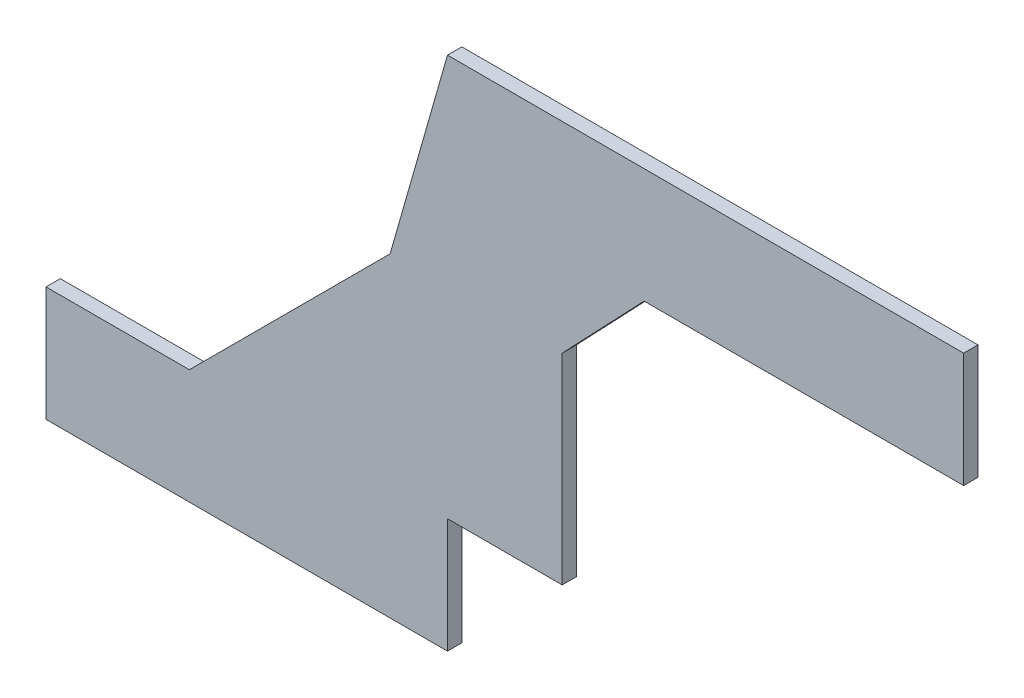
SolidWorks part; units mm, degrees
ref_plane "Front Plane" through (0, 0, 0) normal (0, 0, 1) x (1, 0, 0)
ref_plane "Top Plane" through (0, 0, 0) normal (0, 1, 0) x (1, 0, 0)
ref_plane "Right Plane" through (0, 0, 0) normal (1, 0, 0) x (0, 0, -1)
sketch "Sketch1" plane through (0, 0, 0) normal (0, 0, 1) x (1, 0, 0)
  line L0 (0, 0) -> (76.2, 0) construction
  line L1 (76.2, 0) -> (76.2, 88.9) construction
  line L2 (76.2, 88.9) -> (203.2, 88.9) construction
  line L3 (0, -12.7) -> (88.9, -12.7)
  line L4 (88.9, -12.7) -> (88.9, 12.7)
  line L5 (132.4429, 76.2) -> (203.2, 76.2)
  line L6 (0, 12.7) -> (31.75, 12.7)
  line L7 (114.3, 12.7) -> (114.3, 57.15)
  line L8 (88.9, 101.6) -> (203.2, 101.6)
  line L9 (0, -12.7) -> (0, 12.7)
  line L10 (203.2, 76.2) -> (203.2, 101.6)
  line L11 (76.2, 57.15) -> (88.9, 101.6)
  line L12 (88.9, 12.7) -> (114.3, 12.7)
  line L13 (114.3, 57.15) -> (132.4429, 76.2)
  line L14 (76.2, 57.15) -> (31.75, 12.7)
  line L16 (0, 12.7) -> (63.5, 12.7) construction
  line L17 (63.5, 101.6) -> (203.2, 101.6) construction
  line L18 (63.5, 12.7) -> (63.5, 101.6) construction
  line L19 (88.9, 76.2) -> (203.2, 76.2) construction
  line L20 (88.9, -12.7) -> (88.9, 76.2) construction
  dimension "D1" = 76.2
  dimension "D2" = 88.9
  dimension "D3" = 127
  dimension "D6" = 44.45
  dimension "D4" = 12.7
  dimension "D5" = 12.7
extrude "Boss-Extrude1" add sketch "Sketch1" along normal blind 3.175
